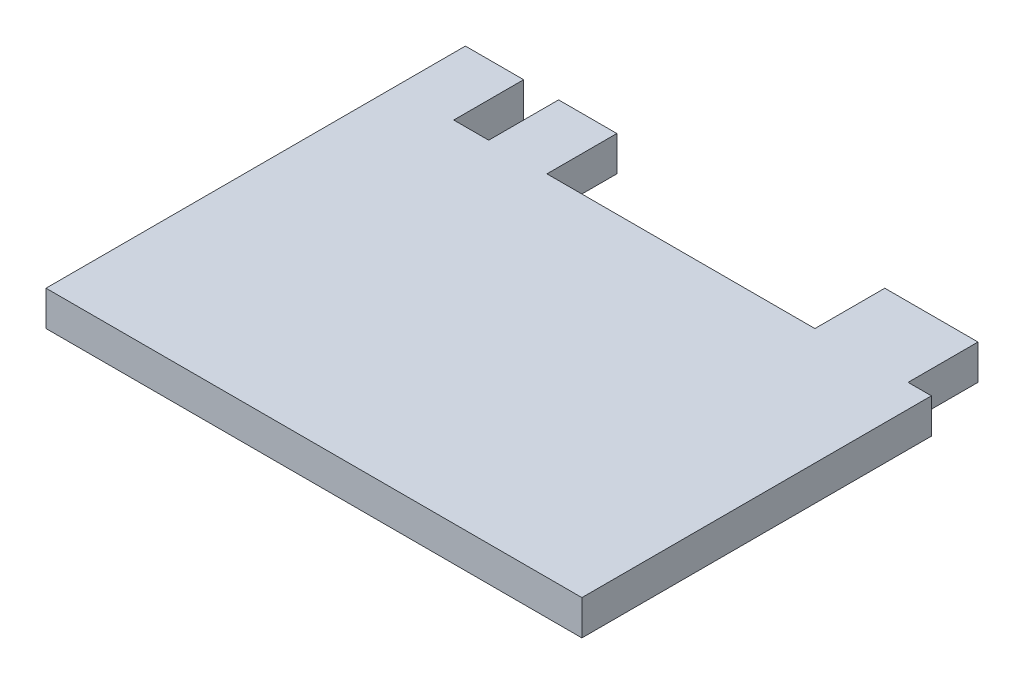
SolidWorks part; units mm, degrees
ref_plane "Front Plane" through (0, 0, 0) normal (0, 0, 1) x (1, 0, 0)
ref_plane "Top Plane" through (0, 0, 0) normal (0, 1, 0) x (1, 0, 0)
ref_plane "Right Plane" through (0, 0, 0) normal (1, 0, 0) x (0, 0, -1)
sketch "Эскиз1" plane through (0, 0, 0) normal (0, 1, 0) x (1, 0, 0)
  line L0 (10.5, 18) -> (6.5, 18)
  line L1 (0, 0) -> (-11.5, 0)
  line L2 (0, 0) -> (11.5, 0)
  line L3 (11.5, 0) -> (11.5, 15)
  line L4 (11.5, 15) -> (10.5, 15)
  line L5 (-11.5, 15) -> (-11.5, 0)
  line L6 (6.5, 18) -> (6.5, 15)
  line L7 (6.5, 15) -> (-5, 15)
  line L8 (10.5, 15) -> (10.5, 18)
  line L9 (-11.5, 15) -> (-11.5, 18)
  line L10 (-11.5, 18) -> (-9, 18)
  line L11 (-9, 18) -> (-9, 15)
  line L12 (-7.5, 15) -> (-9, 15)
  line L13 (-7.5, 18) -> (-7.5, 15)
  line L14 (-7.5, 18) -> (-5, 18)
  line L15 (-5, 18) -> (-5, 15)
  dimension "D1" = 6.5
  dimension "D2" = 10.5
  dimension "D3" = 11.5
  dimension "D4" = 7.5
  dimension "D5" = 15
  dimension "D6" = 18
extrude "Бобышка-Вытянуть1" add sketch "Эскиз1" along normal blind 1.5
